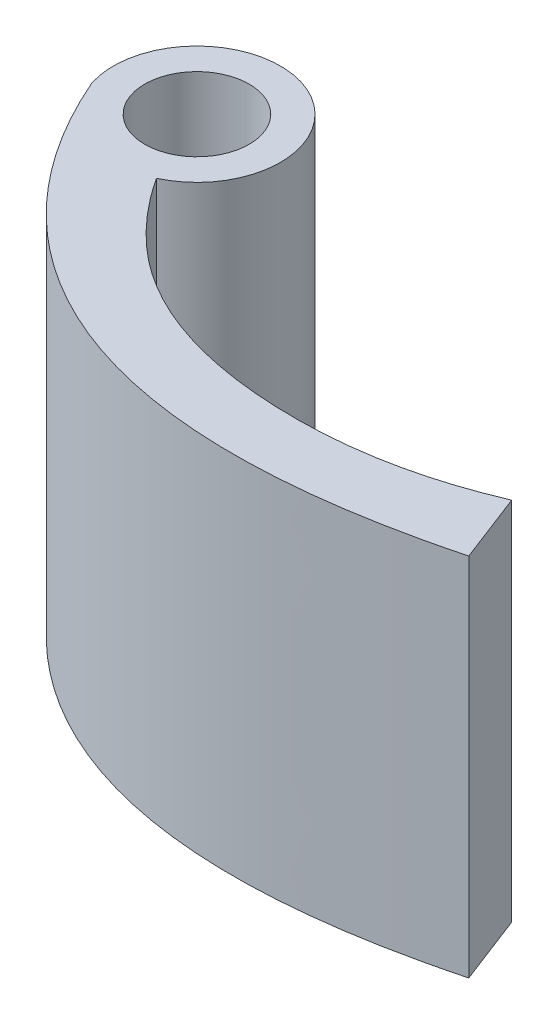
SolidWorks part; units mm, degrees
ref_plane "Front Plane" through (0, 0, 0) normal (0, 0, 1) x (1, 0, 0)
ref_plane "Top Plane" through (0, 0, 0) normal (0, 1, 0) x (1, 0, 0)
ref_plane "Right Plane" through (0, 0, 0) normal (1, 0, 0) x (0, 0, -1)
sketch "Sketch1" plane through (0, 0, 0) normal (0, 1, 0) x (1, 0, 0)
  line L0 (23.5419, -8.4685) -> (24.8317, -11.8149)
  circle A0 centre (0, 0) radius 2.5
  arc A1 (1.6896, -3.6256) -> (-3.8056, -1.2319) centre (0, 0) ccw
  spline S2 degree 3 poles (-3.8056, -1.2319) (-3.5289, -1.8676) (-2.9187, -3.1256) (-1.5151, -5.4545) (0.6234, -8.0456) (3.7819, -10.498) (7.4187, -12.1897) (11.3898, -13.1105) (15.6096, -13.3267) (19.3308, -12.9773) (22.4196, -12.4101) (24.0386, -12.0238) (24.8317, -11.8149) knots 0 0 0 0 0.0625 0.125 0.25 0.375 0.5 0.625 0.75 0.875 0.9375 1 1 1 1
  spline S3 degree 2 poles (1.6896, -3.6256) (2.7203, -5.2185) (7.8052, -10.0394) (19.0409, -10.4028) (23.5419, -8.4685) knots 0.175056 0.175056 0.175056 0.314868 0.704792 1 1 1
  dimension "D1" = 5
  dimension "D2" = 8
extrude "Boss-Extrude1" add sketch "Sketch1" along normal blind 17.5
